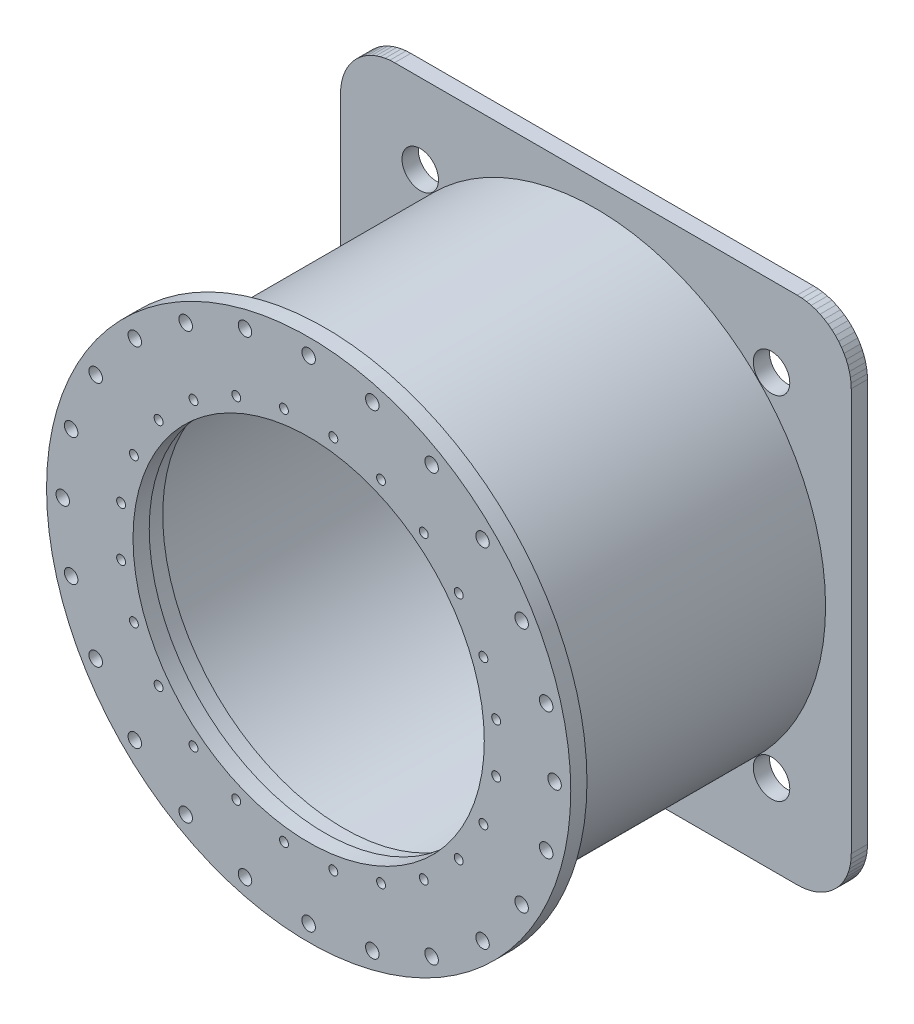
SolidWorks part; units mm, degrees
material "灰铸铁"
ref_plane "前视基准面" through (0, 0, 0) normal (0, 0, 1) x (1, 0, 0)
ref_plane "上视基准面" through (0, 0, 0) normal (0, 1, 0) x (1, 0, 0)
ref_plane "右视基准面" through (0, 0, 0) normal (1, 0, 0) x (0, 0, -1)
other "Configuration Table"
sketch "草图1" plane through (0, 0, 0) normal (0, 0, 1) x (1, 0, 0)
  line L0 (94.5, 74.5) -> (94.4239, 76.2431)
  line L1 (94.4239, 76.2431) -> (94.1962, 77.973)
  line L2 (94.1962, 77.973) -> (93.8185, 79.6764)
  line L3 (93.8185, 79.6764) -> (93.2939, 81.3404)
  line L4 (93.2939, 81.3404) -> (92.6262, 82.9524)
  line L5 (92.6262, 82.9524) -> (91.8205, 84.5)
  line L6 (91.8205, 84.5) -> (90.883, 85.9715)
  line L7 (90.883, 85.9715) -> (89.8209, 87.3558)
  line L8 (89.8209, 87.3558) -> (88.6421, 88.6421)
  line L9 (88.6421, 88.6421) -> (87.3558, 89.8209)
  line L10 (87.3558, 89.8209) -> (85.9715, 90.883)
  line L11 (85.9715, 90.883) -> (84.5, 91.8205)
  line L12 (84.5, 91.8205) -> (82.9524, 92.6262)
  line L13 (82.9524, 92.6262) -> (81.3404, 93.2939)
  line L14 (81.3404, 93.2939) -> (79.6764, 93.8185)
  line L15 (79.6764, 93.8185) -> (77.973, 94.1962)
  line L16 (77.973, 94.1962) -> (76.2431, 94.4239)
  line L17 (76.2431, 94.4239) -> (74.5, 94.5)
  line L18 (74.5, 94.5) -> (-74.5, 94.5)
  line L19 (-74.5, 94.5) -> (-76.2431, 94.4239)
  line L20 (-76.2431, 94.4239) -> (-77.973, 94.1962)
  line L21 (-77.973, 94.1962) -> (-79.6764, 93.8185)
  line L22 (-79.6764, 93.8185) -> (-81.3404, 93.2939)
  line L23 (-81.3404, 93.2939) -> (-82.9524, 92.6262)
  line L24 (-82.9524, 92.6262) -> (-84.5, 91.8205)
  line L25 (-84.5, 91.8205) -> (-85.9715, 90.883)
  line L26 (-85.9715, 90.883) -> (-87.3558, 89.8209)
  line L27 (-87.3558, 89.8209) -> (-88.6421, 88.6421)
  line L28 (-88.6421, 88.6421) -> (-89.8209, 87.3558)
  line L29 (-89.8209, 87.3558) -> (-90.883, 85.9715)
  line L30 (-90.883, 85.9715) -> (-91.8205, 84.5)
  line L31 (-91.8205, 84.5) -> (-92.6262, 82.9524)
  line L32 (-92.6262, 82.9524) -> (-93.2939, 81.3404)
  line L33 (-93.2939, 81.3404) -> (-93.8185, 79.6764)
  line L34 (-93.8185, 79.6764) -> (-94.1962, 77.973)
  line L35 (-94.1962, 77.973) -> (-94.4239, 76.2431)
  line L36 (-94.4239, 76.2431) -> (-94.5, 74.5)
  line L37 (-94.5, 74.5) -> (-94.5, -74.5)
  line L38 (-94.5, -74.5) -> (-94.4239, -76.2431)
  line L39 (-94.4239, -76.2431) -> (-94.1962, -77.973)
  line L40 (-94.1962, -77.973) -> (-93.8185, -79.6764)
  line L41 (-93.8185, -79.6764) -> (-93.2939, -81.3404)
  line L42 (-93.2939, -81.3404) -> (-92.6262, -82.9524)
  line L43 (-92.6262, -82.9524) -> (-91.8205, -84.5)
  line L44 (-91.8205, -84.5) -> (-90.883, -85.9715)
  line L45 (-90.883, -85.9715) -> (-89.8209, -87.3558)
  line L46 (-89.8209, -87.3558) -> (-88.6421, -88.6421)
  line L47 (-88.6421, -88.6421) -> (-87.3558, -89.8209)
  line L48 (-87.3558, -89.8209) -> (-85.9715, -90.883)
  line L49 (-85.9715, -90.883) -> (-84.5, -91.8205)
  line L50 (-84.5, -91.8205) -> (-82.9524, -92.6262)
  line L51 (-82.9524, -92.6262) -> (-81.3404, -93.2939)
  line L52 (-81.3404, -93.2939) -> (-79.6764, -93.8185)
  line L53 (-79.6764, -93.8185) -> (-77.973, -94.1962)
  line L54 (-77.973, -94.1962) -> (-76.2431, -94.4239)
  line L55 (-76.2431, -94.4239) -> (-74.5, -94.5)
  line L56 (-74.5, -94.5) -> (74.5, -94.5)
  line L57 (74.5, -94.5) -> (76.2431, -94.4239)
  line L58 (76.2431, -94.4239) -> (77.973, -94.1962)
  line L59 (77.973, -94.1962) -> (79.6764, -93.8185)
  line L60 (79.6764, -93.8185) -> (81.3404, -93.2939)
  line L61 (81.3404, -93.2939) -> (82.9524, -92.6262)
  line L62 (82.9524, -92.6262) -> (84.5, -91.8205)
  line L63 (84.5, -91.8205) -> (85.9715, -90.883)
  line L64 (85.9715, -90.883) -> (87.3558, -89.8209)
  line L65 (87.3558, -89.8209) -> (88.6421, -88.6421)
  line L66 (88.6421, -88.6421) -> (89.8209, -87.3558)
  line L67 (89.8209, -87.3558) -> (90.883, -85.9715)
  line L68 (90.883, -85.9715) -> (91.8205, -84.5)
  line L69 (91.8205, -84.5) -> (92.6262, -82.9524)
  line L70 (92.6262, -82.9524) -> (93.2939, -81.3404)
  line L71 (93.2939, -81.3404) -> (93.8185, -79.6764)
  line L72 (93.8185, -79.6764) -> (94.1962, -77.973)
  line L73 (94.1962, -77.973) -> (94.4239, -76.2431)
  line L74 (94.4239, -76.2431) -> (94.5, -74.5)
  line L75 (94.5, -74.5) -> (94.5, 74.5)
extrude "01_SQUARE_FLANGE" add sketch "草图1" along normal blind 6
ref_plane "Plane_Tube" through (0, 0, 6) normal (0, 0, 1) x (1, 0, 0)
sketch "草图2" plane through (0, 0, 6) normal (0, 0, 1) x (1, 0, 0)
  circle A0 centre (0, 0) radius 85
extrude "02_TUBE_D170" add sketch "草图2" along normal blind 100.3
ref_plane "Plane_RFlange" through (0, 0, 106.3) normal (0, 0, 1) x (1, 0, 0)
sketch "草图3" plane through (0, 0, 106.3) normal (0, 0, 1) x (1, 0, 0)
  circle A0 centre (0, 0) radius 97
extrude "03_FLANGE_D194" add sketch "草图3" along normal blind 6
sketch "草图4" plane through (0, 0, 0) normal (0, 0, 1) x (1, 0, 0)
  circle A0 centre (0, 0) radius 79
extrude "04_BORE_D158" cut sketch "草图4" along normal blind 10
ref_plane "Plane_B150" through (0, 0, 10) normal (0, 0, 1) x (1, 0, 0)
sketch "草图5" plane through (0, 0, 10) normal (0, 0, 1) x (1, 0, 0)
  circle A0 centre (0, 0) radius 75
extrude "05_BORE_D150" cut sketch "草图5" along normal blind 89.3
ref_plane "Plane_134" through (0, 0, 99.3) normal (0, 0, 1) x (1, 0, 0)
sketch "草图6" plane through (0, 0, 99.3) normal (0, 0, 1) x (1, 0, 0)
  circle A0 centre (0, 0) radius 67
extrude "06_BORE_D134" cut sketch "草图6" along normal blind 7
sketch "草图7" plane through (0, 0, 106.3) normal (0, 0, 1) x (1, 0, 0)
  circle A0 centre (0, 0) radius 65
extrude "07_BORE_D130" cut sketch "草图7" along normal blind 6
sketch "草图8" plane through (0, 0, 106.3) normal (0, 0, 1) x (1, 0, 0)
  circle A0 centre (91, 0) radius 2.5
  circle A1 centre (87.8993, 23.5525) radius 2.5
  circle A2 centre (78.8083, 45.5) radius 2.5
  circle A3 centre (64.3467, 64.3467) radius 2.5
  circle A4 centre (45.5, 78.8083) radius 2.5
  circle A5 centre (23.5525, 87.8993) radius 2.5
  circle A6 centre (0, 91) radius 2.5
  circle A7 centre (-23.5525, 87.8993) radius 2.5
  circle A8 centre (-45.5, 78.8083) radius 2.5
  circle A9 centre (-64.3467, 64.3467) radius 2.5
  circle A10 centre (-78.8083, 45.5) radius 2.5
  circle A11 centre (-87.8993, 23.5525) radius 2.5
  circle A12 centre (-91, 0) radius 2.5
  circle A13 centre (-87.8993, -23.5525) radius 2.5
  circle A14 centre (-78.8083, -45.5) radius 2.5
  circle A15 centre (-64.3467, -64.3467) radius 2.5
  circle A16 centre (-45.5, -78.8083) radius 2.5
  circle A17 centre (-23.5525, -87.8993) radius 2.5
  circle A18 centre (0, -91) radius 2.5
  circle A19 centre (23.5525, -87.8993) radius 2.5
  circle A20 centre (45.5, -78.8083) radius 2.5
  circle A21 centre (64.3467, -64.3467) radius 2.5
  circle A22 centre (78.8083, -45.5) radius 2.5
  circle A23 centre (87.8993, -23.5525) radius 2.5
extrude "08_HOLES_24_D5" cut sketch "草图8" along normal blind 6
sketch "草图9" plane through (0, 0, 0) normal (0, 0, 1) x (1, 0, 0)
  circle A0 centre (-65, -65) radius 6.75
  circle A1 centre (-65, 65) radius 6.75
  circle A2 centre (65, -65) radius 6.75
  circle A3 centre (65, 65) radius 6.75
extrude "09_HOLES_4_D13.5" cut sketch "草图9" along normal blind 6
sketch "草图10" plane through (0, 0, 106.3) normal (0, 0, 1) x (1, 0, 0)
  circle A0 centre (69.4011, 9.1368) radius 1.65
  circle A1 centre (64.6716, 26.7878) radius 1.65
  circle A2 centre (55.5347, 42.6133) radius 1.65
  circle A3 centre (42.6133, 55.5347) radius 1.65
  circle A4 centre (26.7878, 64.6716) radius 1.65
  circle A5 centre (9.1368, 69.4011) radius 1.65
  circle A6 centre (-9.1368, 69.4011) radius 1.65
  circle A7 centre (-26.7878, 64.6716) radius 1.65
  circle A8 centre (-42.6133, 55.5347) radius 1.65
  circle A9 centre (-55.5347, 42.6133) radius 1.65
  circle A10 centre (-64.6716, 26.7878) radius 1.65
  circle A11 centre (-69.4011, 9.1368) radius 1.65
  circle A12 centre (-69.4011, -9.1368) radius 1.65
  circle A13 centre (-64.6716, -26.7878) radius 1.65
  circle A14 centre (-55.5347, -42.6133) radius 1.65
  circle A15 centre (-42.6133, -55.5347) radius 1.65
  circle A16 centre (-26.7878, -64.6716) radius 1.65
  circle A17 centre (-9.1368, -69.4011) radius 1.65
  circle A18 centre (9.1368, -69.4011) radius 1.65
  circle A19 centre (26.7878, -64.6716) radius 1.65
  circle A20 centre (42.6133, -55.5347) radius 1.65
  circle A21 centre (55.5347, -42.6133) radius 1.65
  circle A22 centre (64.6716, -26.7878) radius 1.65
  circle A23 centre (69.4011, -9.1368) radius 1.65
extrude "10_HOLES_24_M4" cut sketch "草图10" along normal blind 6
